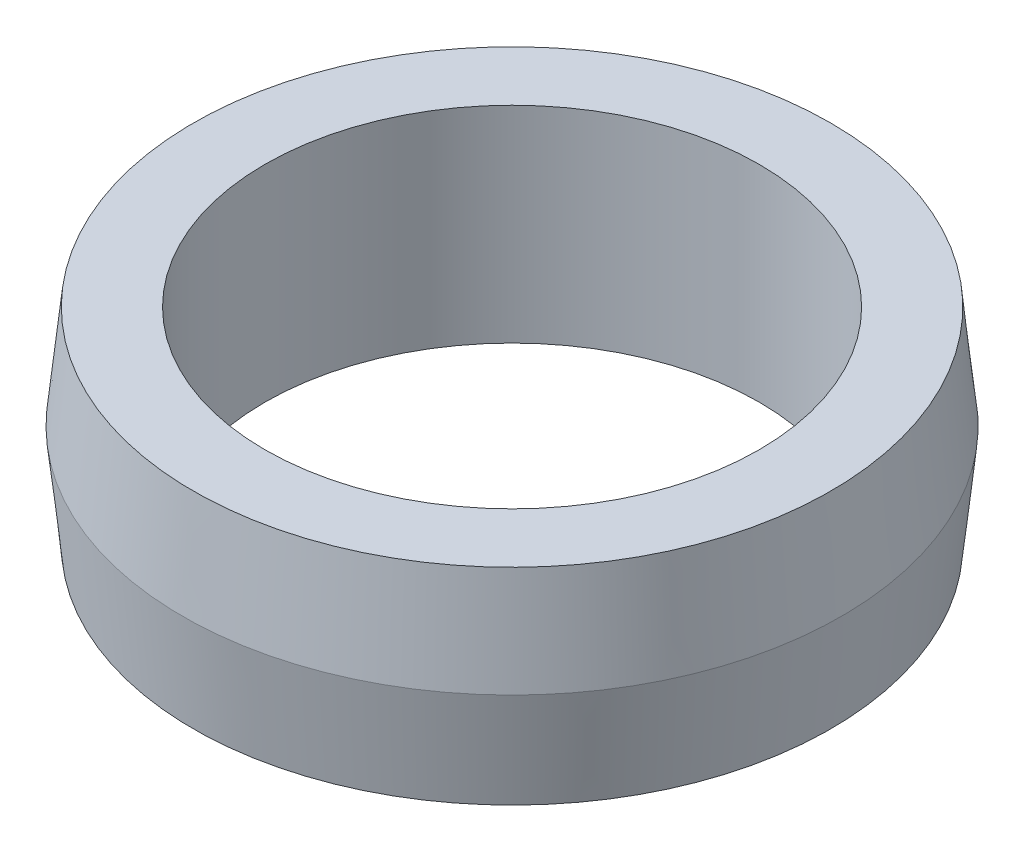
SolidWorks part; units mm, degrees
material "BUTYL"
ref_plane "Alzado" through (0, 0, 0) normal (0, 0, 1) x (1, 0, 0)
ref_plane "Planta" through (0, 0, 0) normal (0, 1, 0) x (1, 0, 0)
ref_plane "Vista lateral" through (0, 0, 0) normal (1, 0, 0) x (0, 0, -1)
sketch "Croquis1" plane through (0, 0, 0) normal (0, 1, 0) x (1, 0, 0)
  circle A0 centre (0, 0) radius 38.1
  circle A1 centre (0, 0) radius 50.8
  dimension "D1" = 101.6
  dimension "D2" = 76.2
extrude "Saliente-Extruir1" add sketch "Croquis1" along normal blind 31.75
sketch "Croquis3" plane through (0, 0, 0) normal (1, 0, 0) x (0, 0, -1)
  line L0 (-50.8, 15.875) -> (-49.1315, 31.75)
  line L1 (-50.8, 31.75) -> (-50.8, 0) construction
  line L2 (50.8, 31.75) -> (-50.8, 31.75) construction
  line L3 (-49.1315, 31.75) -> (-49.1315, 0) construction
  line L4 (-49.1315, 0) -> (-50.8, 15.875)
  line L5 (-49.1315, 31.75) -> (-69.1315, 31.75)
  line L6 (-69.1315, 31.75) -> (-69.1315, 0)
  line L7 (-69.1315, 0) -> (-49.1315, 0)
  line L8 (0, 0) -> (0, 64.566) construction
  dimension "D1" = 6
  dimension "D2" = 20
revolve "Cortar-Revolución1" cut sketch "Croquis3" angle 360 about L8
